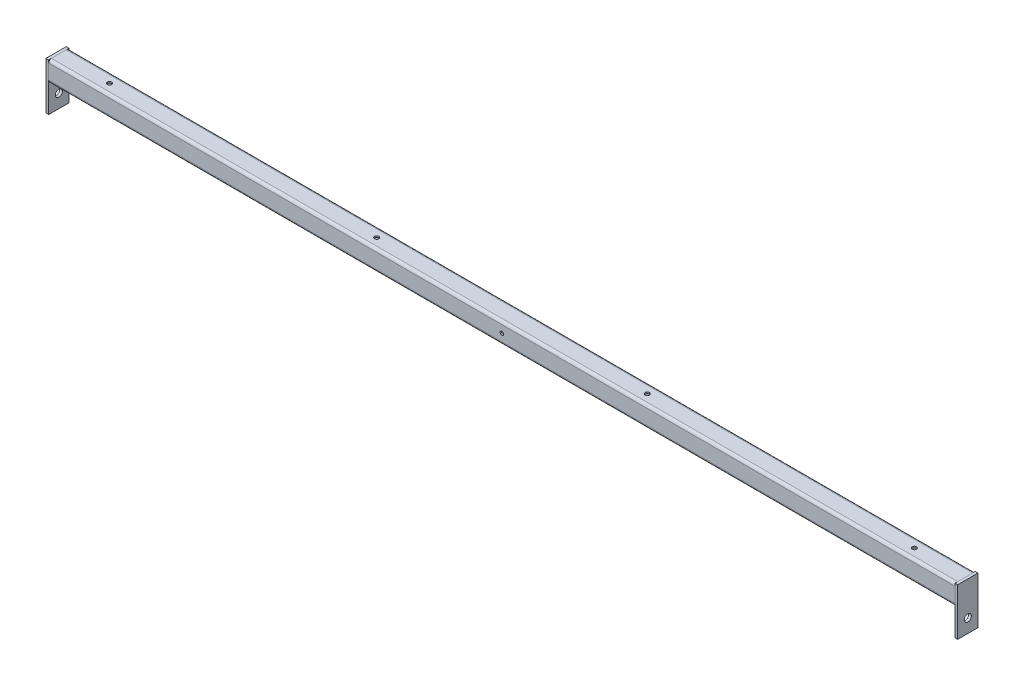
SolidWorks part; units mm, degrees
other "DetailItem1"
other "DetailItem2"
other "Weld Folder"
other "Weld Bead1"
other "Weld Bead2"
material "AISI 304"
ref_plane "Front Plane" through (0, 0, 0) normal (0, 0, 1) x (1, 0, 0)
ref_plane "Top Plane" through (0, 0, 0) normal (0, 1, 0) x (1, 0, 0)
ref_plane "Right Plane" through (0, 0, 0) normal (1, 0, 0) x (0, 0, -1)
sketch3d "3DStructure"
  line L0 (0, 0, 0) -> (0, 70, 0)
  line L2 (1344, 70, 0) -> (1344, 0, 0)
  line L3 (0, 55, 0) -> (1344, 55, 0)
  dimension "D3" = 15
  dimension "D1" = 1344
  dimension "D2" = 15
  dimension "D4" = 70
other "Square tube - configured 30 X 30 X 2"
ref_plane "Plane1" through (0, 55, 0) normal (1, 0, 0) x (0, 0, -1)
sketch "Sketch1" plane through (0, 55, 0) normal (1, 0, 0) x (0, 0, -1)
  line L0 (-11, -13) -> (11, -13)
  line L1 (-13, -11) -> (-13, 11)
  line L2 (11, 13) -> (-11, 13)
  line L3 (13, 11) -> (13, -11)
  line L4 (-11, -15) -> (11, -15)
  line L5 (-15, -11) -> (-15, 11)
  line L6 (11, 15) -> (-11, 15)
  line L7 (15, 11) -> (15, -11)
  arc A0 (15, 11) -> (11, 15) centre (11, 11) ccw
  arc A1 (11, -15) -> (15, -11) centre (11, -11) ccw
  arc A2 (-15, -11) -> (-11, -15) centre (-11, -11) ccw
  arc A3 (-11, 15) -> (-15, 11) centre (-11, 11) ccw
  arc A4 (-11, 13) -> (-13, 11) centre (-11, 11) ccw
  arc A5 (13, 11) -> (11, 13) centre (11, 11) ccw
  arc A6 (11, -13) -> (13, -11) centre (11, -11) ccw
  arc A7 (-13, -11) -> (-11, -13) centre (-11, -11) ccw
  point P0 (-15, 0)
  point P1 (15, 0)
  point P2 (0, 15)
  point P3 (0, -15)
  point P4 (0, 0)
  point P5 (-15, -15)
  point P6 (15, -15)
  point P7 (15, 15)
  point P8 (-15, 15)
  point P33 (0, 0)
  dimension "D1" = 4
  dimension "Thickness" = 2
  dimension "V_leg" = 30
other "Steel bar - configured 30 X 2"
ref_plane "Plane2" through (0, 0, 0) normal (0, 1, 0) x (1, 0, 0)
sketch "Sketch11" plane through (0, 0, 0) normal (0, 1, 0) x (1, 0, 0)
  line L9 (2, -15) -> (-2, -15)
  line L10 (2, -15) -> (2, 15)
  line L11 (2, 15) -> (-2, 15)
  line L12 (-2, -15) -> (-2, 15)
  line L13 (2, -15) -> (-2, 15) construction
  line L14 (2, 15) -> (-2, -15) construction
  point P4 (0, 0)
  point P33 (0, 0)
  point P35 (0, 0)
  dimension "D2" = 4
  dimension "D3" = 30
other "Trim/Extend1"
hole_wizard "Ø10.5 (10.5) Frame Mount Holes" positions "Sketch12" profile "Sketch13" hole size "Ø10.5" standard "ANSI Metric" end condition through all
sketch "Sketch12" plane through (1346, 0, 0) normal (1, 0, 0) x (0, 0, -1)
  line L0 (-15, 0) -> (15, 0) construction
  point P0 (0, 20)
  dimension "D1" = 20
sketch "Sketch13" plane through (1346, 20, 0) normal (0, 1, 0) x (0, 0, -1)
  line L0 (0, 0) -> (0, 1348)
  line L1 (0, 1348) -> (5.25, 1348)
  line L2 (5.25, 1348) -> (5.25, 0)
  line L5 (5.25, 0) -> (0, 0)
  line L11 (0, -6.35) -> (0, 107.95) construction
  dimension "Thru Hole Dia." = 10.5
  dimension "Thru Hole Depth" = 1348
hole_wizard "Ø10.5 (10.5) PC Shelf Mount Hole" [suppressed] positions "Sketch14" profile "Sketch16" hole size "Ø10.5" standard "ANSI Metric"
sketch "Sketch14" plane through (0, 0, 15) normal (0, 0, 1) x (1, 0, 0)
  line L0 (1346, 0) -> (1346, 70) construction
  line L2 (1342, 44) -> (1342, 66) construction
  point P0 (1166, 55)
  point P11 (1342, 55)
  dimension "D1" = 180
sketch "Sketch16" plane through (1166, 55, 15) normal (1, 0, 0) x (0, -1, 0)
  line L0 (0, 0) -> (0, 30)
  line L1 (0, 30) -> (5.25, 30)
  line L2 (5.25, 30) -> (5.25, 0)
  line L5 (5.25, 0) -> (0, 0)
  line L11 (0, -6.35) -> (0, 107.95) construction
  dimension "Thru Hole Dia." = 10.5
  dimension "Thru Hole Depth" = 30
hole_wizard "Ø5.2 (5.2) Wall Mount Hole" positions "Sketch17" profile "Sketch18" hole size "Ø5.2" standard "ANSI Metric" end condition through all
sketch "Sketch17" plane through (0, 0, 15) normal (0, 0, 1) x (1, 0, 0)
  line L1 (2, 66) -> (2, 44) construction
  line L2 (-2, 70) -> (-2, 0) construction
  point P0 (672, 55)
  point P10 (2, 55)
  dimension "D1" = 674
sketch "Sketch18" plane through (672, 55, 15) normal (1, 0, 0) x (0, -1, 0)
  line L0 (0, 0) -> (0, 30)
  line L1 (0, 30) -> (2.6, 30)
  line L2 (2.6, 30) -> (2.6, 0)
  line L5 (2.6, 0) -> (0, 0)
  line L11 (0, -6.35) -> (0, 107.95) construction
  dimension "Thru Hole Dia." = 5.2
  dimension "Thru Hole Depth" = 30
hole_wizard "Ø4.2 (4.2) PC Shelf Table Mount Hole" [suppressed] positions "Sketch19" profile "Sketch20" hole size "Ø4.2" standard "ANSI Metric"
sketch "Sketch19" plane through (0, 40, 0) normal (0, -1, 0) x (-1, 0, 0)
  line L0 (-1346, -15) -> (-1346, 15) construction
  point P0 (-1271, 0)
  dimension "D1" = 75
sketch "Sketch20" plane through (1271, 40, 0) normal (1, 0, 0) x (0, 0, -1)
  line L0 (0, 0) -> (0, 30)
  line L1 (0, 30) -> (2.1, 30)
  line L2 (2.1, 30) -> (2.1, 0)
  line L5 (2.1, 0) -> (0, 0)
  line L11 (0, -6.35) -> (0, 107.95) construction
  dimension "Thru Hole Dia." = 4.2
  dimension "Thru Hole Depth" = 30
hole_wizard "M6 Clearance Hole table mount" positions "Sketch21" profile "Sketch22" hole size "M6" standard "ANSI Metric" end condition through all
sketch "Sketch21" plane through (0, 70, 0) normal (0, 1, 0) x (1, 0, 0)
  line L0 (672, -44.1343) -> (672, 40.0748) construction
  line L2 (1342, -15) -> (2, -15) construction
  point P0 (77, 0)
  point P2 (472, 0)
  point P4 (872, 0)
  point P6 (1267, 0)
  point P17 (672, -15)
  dimension "D1" = 400
  dimension "D2" = 395
  dimension "D3" = 395
sketch "Sketch22" plane through (77, 70, 0) normal (1, 0, 0) x (0, 0, 1)
  line L0 (0, 0) -> (0, 70)
  line L1 (0, 70) -> (3.2, 70)
  line L2 (3.2, 70) -> (3.2, 0)
  line L5 (3.2, 0) -> (0, 0)
  line L11 (0, -6.35) -> (0, 107.95) construction
  dimension "Thru Hole Dia." = 6.4
  dimension "Thru Hole Depth" = 70
equation "\"D3@3DStructure\"=\"D2@3DStructure\""
equation "\"D2@Sketch21\"=\"D3@Sketch21\""
